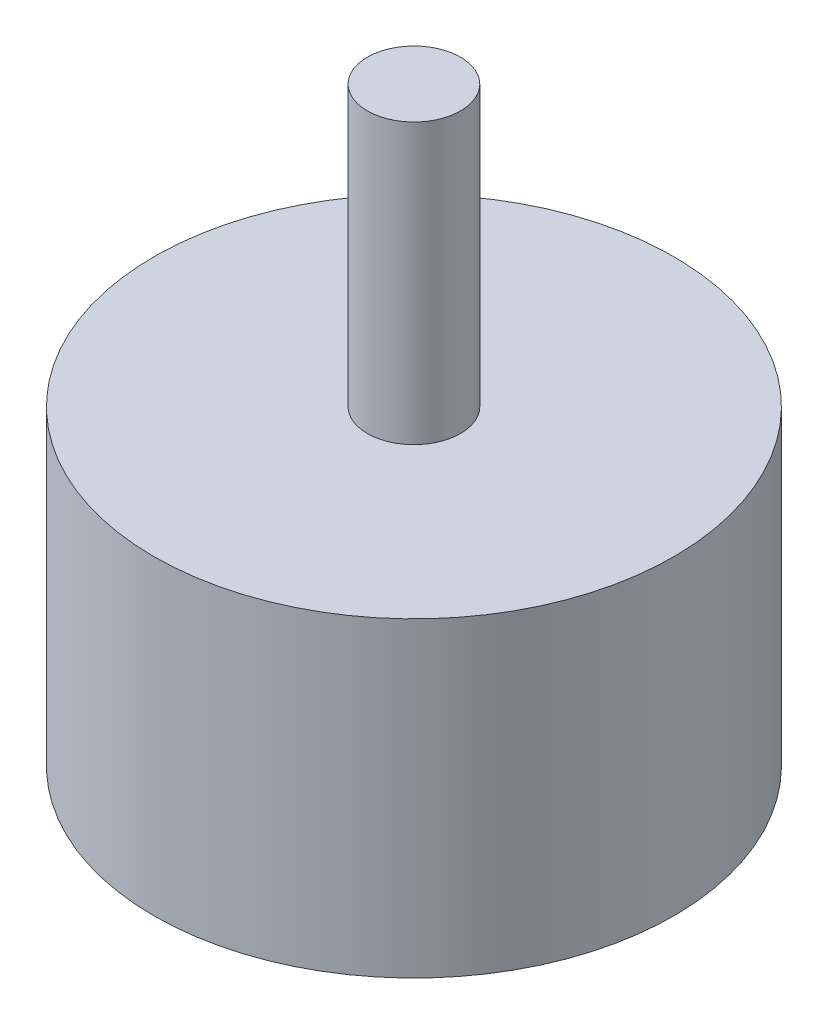
SolidWorks part; units mm, degrees
ref_plane "Front Plane" through (0, 0, 0) normal (0, 0, 1) x (1, 0, 0)
ref_plane "Top Plane" through (0, 0, 0) normal (0, 1, 0) x (1, 0, 0)
ref_plane "Right Plane" through (0, 0, 0) normal (1, 0, 0) x (0, 0, -1)
sketch "Sketch1" plane through (0, 0, 0) normal (0, 1, 0) x (1, 0, 0)
  circle A0 centre (0, 0) radius 13.95
  dimension "D1" = 27.9
extrude "Boss-Extrude1" add sketch "Sketch1" along normal blind 16.7
sketch "Sketch2" plane through (0, 16.7, 0) normal (0, 1, 0) x (1, 0, 0)
  circle A0 centre (0, 0) radius 2.5
  dimension "D1" = 5
extrude "Boss-Extrude2" add sketch "Sketch2" along normal blind 15
